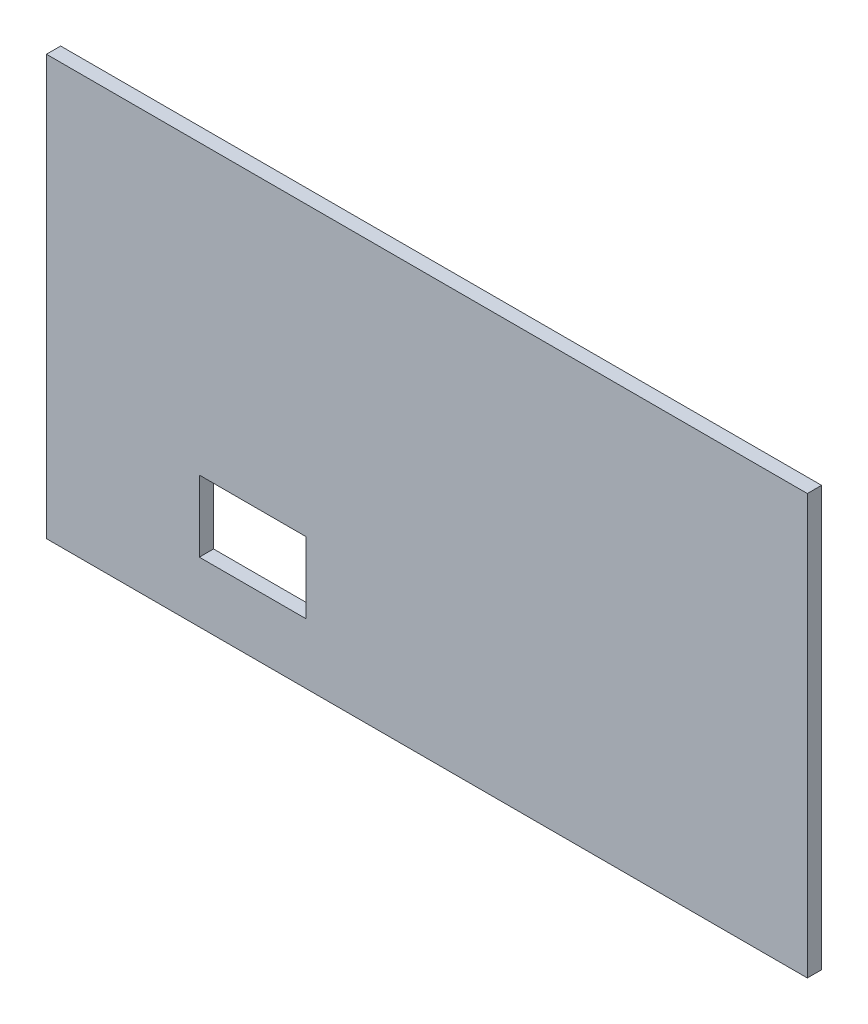
SolidWorks part; units mm, degrees
ref_plane "Plano frontal" through (0, 0, 0) normal (0, 0, 1) x (1, 0, 0)
ref_plane "Plano superior" through (0, 0, 0) normal (0, 1, 0) x (1, 0, 0)
ref_plane "Plano direito" through (0, 0, 0) normal (1, 0, 0) x (0, 0, -1)
sketch "Esboço1" plane through (0, 0, 0) normal (0, 0, 1) x (1, 0, 0)
  line L1 (0, 0) -> (107, 0)
  line L2 (0, 0) -> (0, 59)
  line L3 (0, 59) -> (107, 59)
  line L4 (107, 0) -> (107, 59)
  line L5 (21.5, 8.5) -> (36.5, 8.5)
  line L6 (21.5, 8.5) -> (21.5, 18.5)
  line L7 (21.5, 18.5) -> (36.5, 18.5)
  line L8 (36.5, 8.5) -> (36.5, 18.5)
  dimension "D1" = 107
  dimension "D2" = 59
  dimension "D3" = 15
  dimension "D4" = 10
  dimension "D5" = 8.5
  dimension "D6" = 21.5
extrude "Ressalto-extrusão1" add sketch "Esboço1" along normal blind 2
